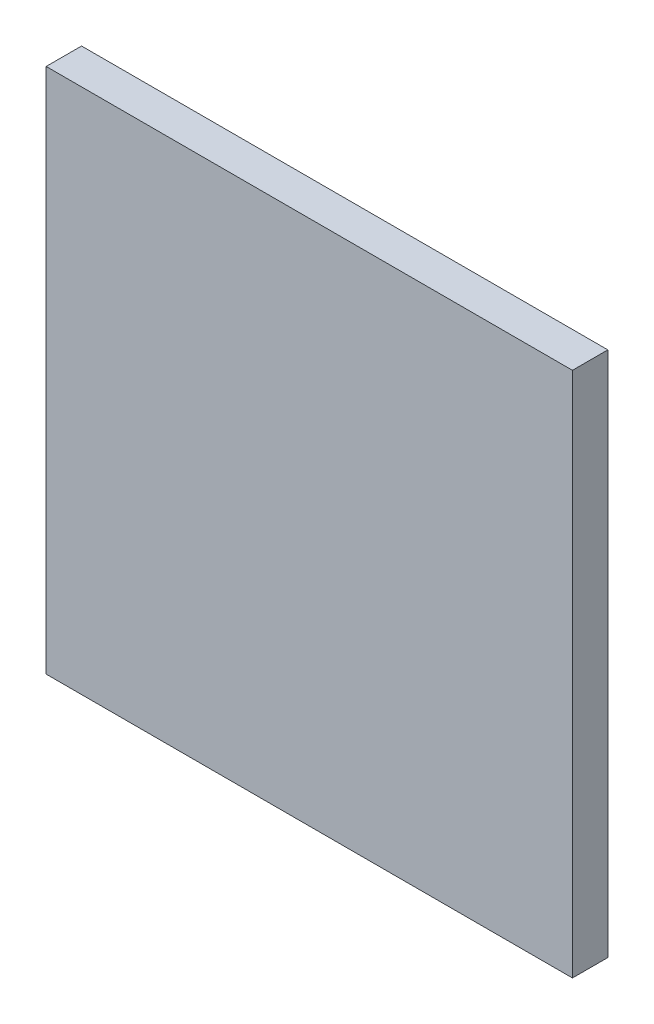
SolidWorks part; units mm, degrees
ref_plane "Front Plane" through (0, 0, 0) normal (0, 0, 1) x (1, 0, 0)
ref_plane "Top Plane" through (0, 0, 0) normal (0, 1, 0) x (1, 0, 0)
ref_plane "Right Plane" through (0, 0, 0) normal (1, 0, 0) x (0, 0, -1)
sketch "Sketch1" plane through (0, 0, 0) normal (0, 0, 1) x (1, 0, 0)
  line L1 (0, 0) -> (8.92, 0)
  line L2 (0, 0) -> (0, -8.92)
  line L3 (0, -8.92) -> (8.92, -8.92)
  line L4 (8.92, 0) -> (8.92, -8.92)
  dimension "D1" = 8.92
extrude "Boss-Extrude1" add sketch "Sketch1" along normal blind 0.6
sketch "Sketch2" plane through (0, 0, 0.6) normal (0, 0, 1) x (1, 0, 0)
  line L0 (2.62, -1.3) -> (2.62, -7.62)
  line L1 (3.22, -1.3) -> (3.22, -7.62)
  line L2 (8.92, -8.92) -> (8.92, 0) construction
  line L3 (0, 0) -> (0, -8.92) construction
  line L4 (0, -8.92) -> (8.92, -8.92) construction
  point P6 (0, -4.46)
  point P7 (2.62, -4.46)
  dimension "D1" = 1.3
  dimension "D2" = 5.7
  dimension "D3" = 0.6
